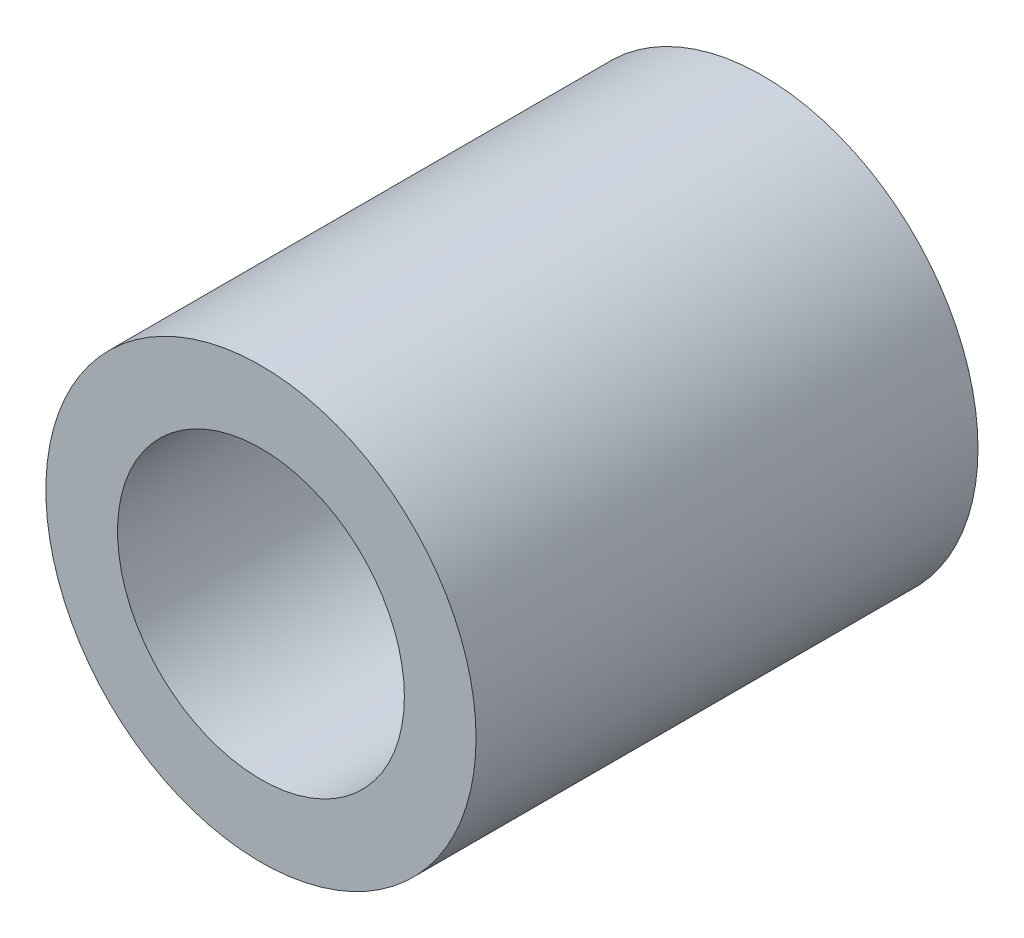
SolidWorks part; units mm, degrees
material "耐油橡胶板 3002"
ref_plane "前视基准面" through (0, 0, 0) normal (0, 0, 1) x (1, 0, 0)
ref_plane "上视基准面" through (0, 0, 0) normal (0, 1, 0) x (1, 0, 0)
ref_plane "右视基准面" through (0, 0, 0) normal (1, 0, 0) x (0, 0, -1)
sketch "草图1" plane through (0, 0, 0) normal (0, 0, 1) x (1, 0, 0)
  circle A0 centre (0, 0) radius 2
  circle A1 centre (0, 0) radius 3
  dimension "D1" = 6
  dimension "D2" = 4
extrude "凸台-拉伸1" add sketch "草图1" along normal blind 7
